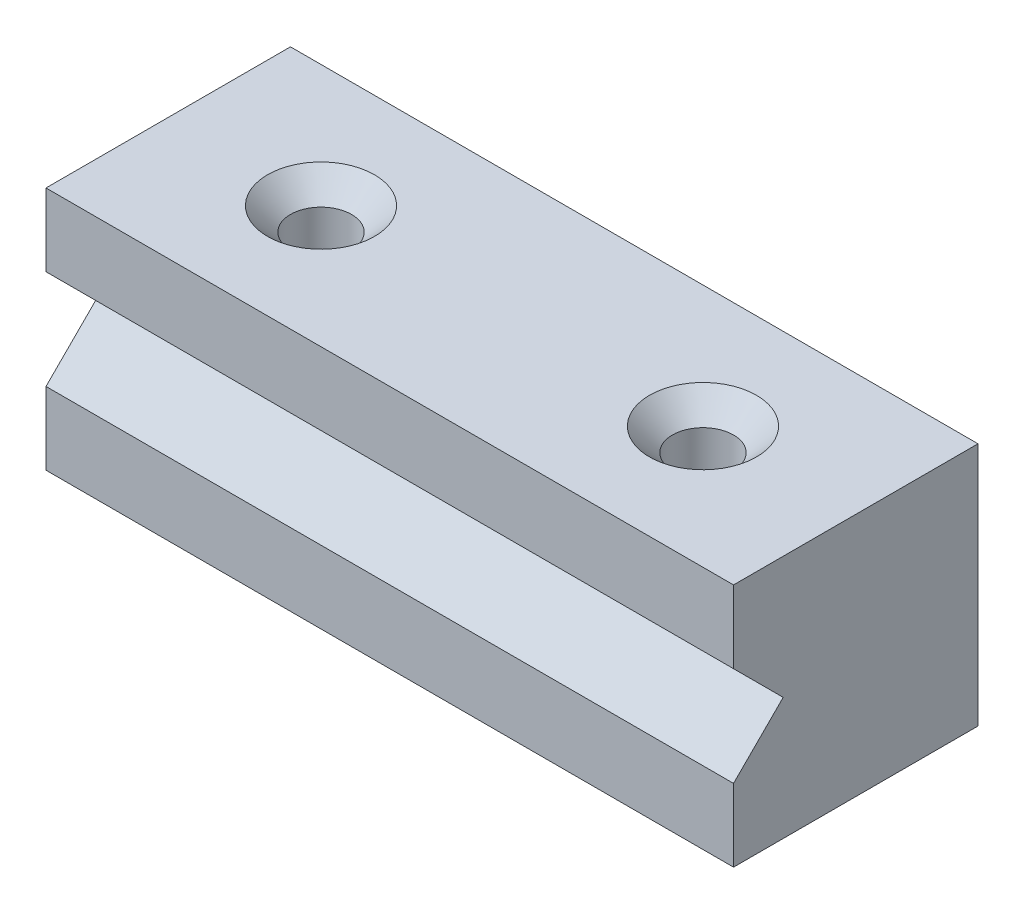
SolidWorks part; units mm, degrees
ref_plane "Front Plane" through (0, 0, 0) normal (0, 0, 1) x (1, 0, 0)
ref_plane "Top Plane" through (0, 0, 0) normal (0, 1, 0) x (1, 0, 0)
ref_plane "Right Plane" through (0, 0, 0) normal (1, 0, 0) x (0, 0, -1)
sketch "Sketch1" plane through (0, 0, 0) normal (0, 0, 1) x (1, 0, 0)
  line L1 (-45, -16) -> (45, -16)
  line L2 (-45, -16) -> (-45, 16)
  line L3 (-45, 16) -> (45, 16)
  line L4 (45, -16) -> (45, 16)
  line L5 (-45, -16) -> (45, 16) construction
  line L6 (-45, 16) -> (45, -16) construction
  point P0 (0, 0)
  dimension "D1" = 90
  dimension "D2" = 32
extrude "Boss-Extrude1" add sketch "Sketch1" along normal mid plane 32
sketch "Sketch2" plane through (45, 0, 0) normal (1, 0, 0) x (0, 0, -1)
  line L0 (-16, 6.5) -> (-9.5, 0)
  line L1 (-16, -16) -> (-16, 16) construction
  line L2 (-9.5, 0) -> (-16, -6.5)
  line L3 (0, 0) -> (-7.5607, 0) construction
  line L4 (-16, 6.5) -> (-16, -6.5)
  dimension "D1" = 13
  dimension "D2" = 90
extrude "Cut-Extrude1" cut sketch "Sketch2" against normal through all
hole_wizard "Ø8.0mm Dowel Hole1" positions "Sketch3" profile "Sketch5" hole size "Ø8.0" standard "ISO" end condition up to next
sketch "Sketch3" plane through (0, 16, 0) normal (0, 1, 0) x (1, 0, 0)
  line L0 (0, 0) -> (0, 12.1265) construction
  point P0 (-25, 0)
  point P2 (25, 0)
  point P9 (0, 0)
  point P10 (0, 0)
  dimension "D1" = 50
sketch "Sketch5" plane through (-25, 16, 0) normal (1, 0, 0) x (0, 0, 1)
  line L0 (0, 0) -> (0, 32)
  line L1 (0, 32) -> (4, 32)
  line L2 (4, 32) -> (4, 0)
  line L5 (4, 0) -> (0, 0)
  line L11 (0, -6.35) -> (0, 107.95) construction
  dimension "Thru Hole Dia." = 8
  dimension "Thru Hole Depth" = 32
chamfer "Chamfer1" distance 3 angle 45 2 edges at (25, 16, 4) (-25, 16, 4)
